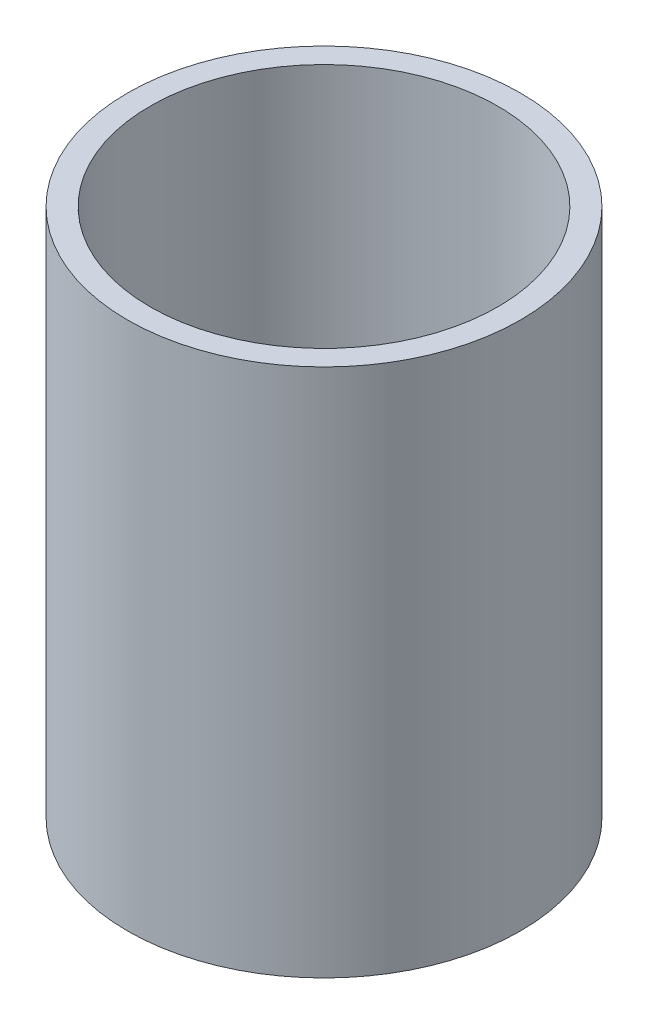
SolidWorks part; units mm, degrees
ref_plane "Front Plane" through (0, 0, 0) normal (0, 0, 1) x (1, 0, 0)
ref_plane "Top Plane" through (0, 0, 0) normal (0, 1, 0) x (1, 0, 0)
ref_plane "Right Plane" through (0, 0, 0) normal (1, 0, 0) x (0, 0, -1)
sketch "Sketch1" plane through (0, 0, 0) normal (0, 1, 0) x (1, 0, 0)
  line L0 (0, 0) -> (0, 27431.1704) construction
  line L1 (0, 0) -> (27431.1704, 0) construction
  circle A0 centre (0, 0) radius 26
  circle A1 centre (0, 0) radius 23
  dimension "D1" = 52
  dimension "D2" = 46
extrude "Boss-Extrude1" add sketch "Sketch1" along normal mid plane 70
